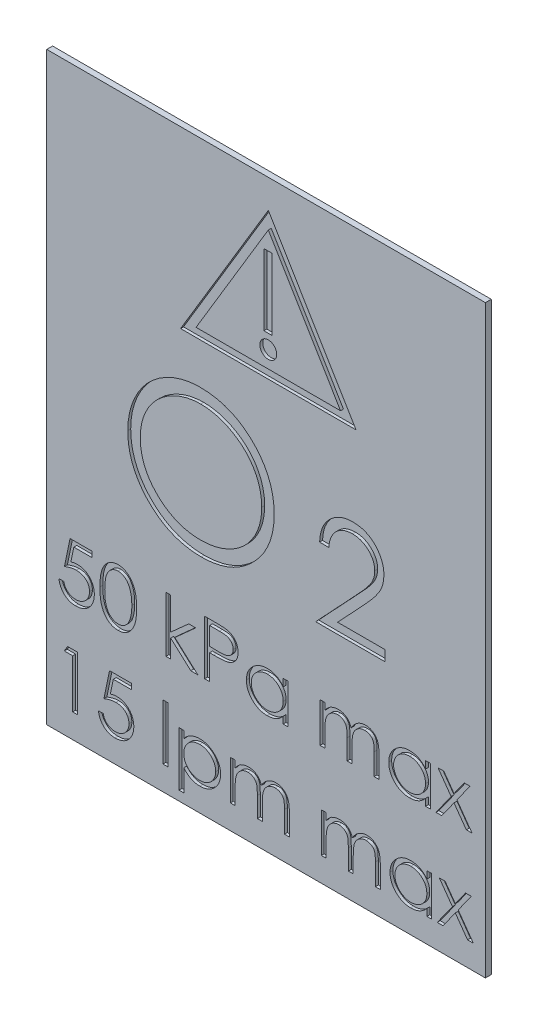
SolidWorks part; units mm, degrees
material "ABS"
ref_plane "Plan de face" through (0, 0, 0) normal (0, 0, 1) x (1, 0, 0)
ref_plane "Plan de dessus" through (0, 0, 0) normal (0, 1, 0) x (1, 0, 0)
ref_plane "Plan de droite" through (0, 0, 0) normal (1, 0, 0) x (0, 0, -1)
sketch "Esquisse1" plane through (0, 0, 0) normal (0, 0, 1) x (1, 0, 0)
  line L0 (0, 5) -> (-15, 5)
  line L2 (0, 5) -> (0, 25)
  line L3 (0, 25) -> (-15, 25)
  line L4 (-15, 5) -> (-15, 25)
  dimension "D1" = 15
extrude "Extrusion1" add sketch "Esquisse1" along normal blind 0.2
sketch "Esquisse2" plane through (0, 0, 0.2) normal (0, 0, 1) x (1, 0, 0)
  line L0 (-10.4237, 19.0215) -> (-4.4237, 19.0215)
  line L1 (-7.4237, 23.4384) -> (-4.9535, 19.3215)
  line L2 (-9.8938, 19.3215) -> (-4.9535, 19.3215)
  line L3 (-9.8938, 19.3215) -> (-7.4237, 23.4384)
  line L4 (-10.4237, 19.0215) -> (-7.4237, 24.0215)
  line L5 (-7.4237, 24.0215) -> (-4.4237, 19.0215)
extrude "Enlèv. mat.-Extru.3" cut sketch "Esquisse2" against normal blind 0.1
sketch "Esquisse3" plane through (0, 0, 0.2) normal (0, 0, 1) x (1, 0, 0)
  line L0 (-7.5737, 22.8138) -> (-7.2922, 22.8138)
  line L1 (-7.5737, 22.8138) -> (-7.5737, 20.3802)
  line L2 (-7.5737, 20.3802) -> (-7.2922, 20.3802)
  line L3 (-7.2922, 22.8138) -> (-7.2922, 20.3802)
  circle A0 centre (-7.4237, 19.897) radius 0.2887
extrude "Enlèv. mat.-Extru.4" cut sketch "Esquisse3" against normal blind 0.1
sketch "Esquisse4" plane through (0, 0, 0.2) normal (0, 0, 1) x (1, 0, 0)
  text T0 "O" font "Century Gothic" height in points 18
extrude "Enlèv. mat.-Extru.5" cut sketch "Esquisse4" against normal blind 0.1
sketch "Esquisse5" plane through (0, 0, 0.2) normal (0, 0, 1) x (1, 0, 0)
  text T0 "2"
extrude "Enlèv. mat.-Extru.6" cut sketch "Esquisse5" against normal blind 0.1
sketch "Esquisse6" plane through (0, 0, 0.2) normal (0, 0, 1) x (1, 0, 0)
  text T0 "50 kPa max" font "Century Gothic" height in points 7
extrude "Enlèv. mat.-Extru.7" cut sketch "Esquisse6" against normal blind 0.1
sketch "Esquisse7" plane through (0, 0, 0.2) normal (0, 0, 1) x (1, 0, 0)
  text T0 "15 lpm max" font "Century Gothic" height in points 7
extrude "Enlèv. mat.-Extru.8" cut sketch "Esquisse7" against normal blind 0.1
